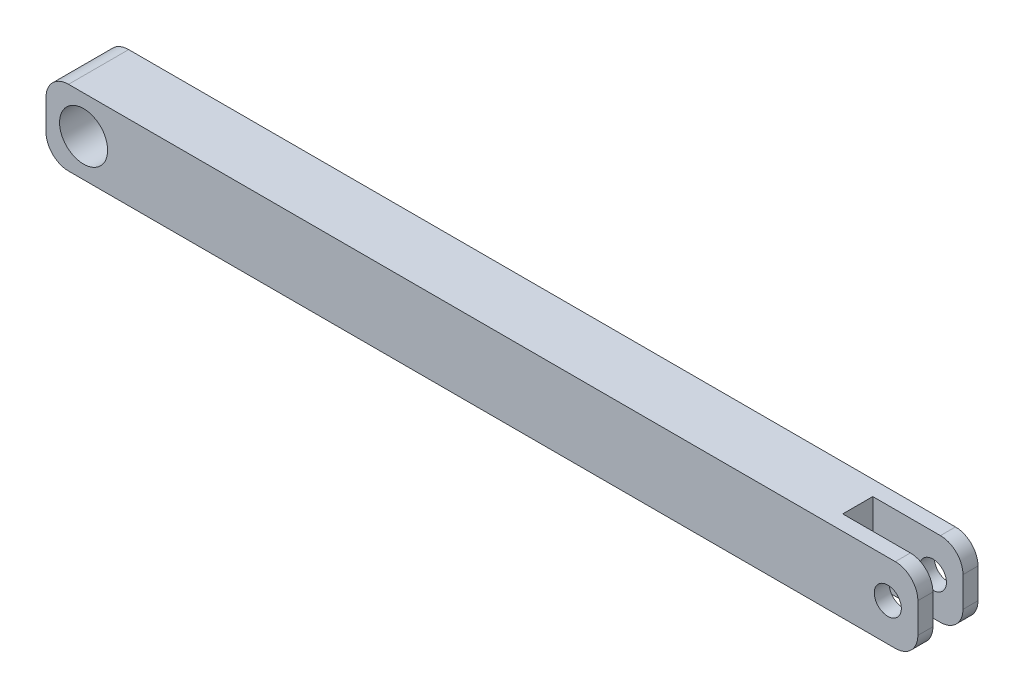
SolidWorks part; units mm, degrees
ref_plane "前视基准面" through (0, 0, 0) normal (0, 0, 1) x (1, 0, 0)
ref_plane "上视基准面" through (0, 0, 0) normal (0, 1, 0) x (1, 0, 0)
ref_plane "右视基准面" through (0, 0, 0) normal (1, 0, 0) x (0, 0, -1)
other "Configuration Table"
sketch "草图5" plane through (0, 0, 0) normal (0, 1, 0) x (1, 0, 0)
  line L0 (0, 0) -> (0, -3)
  line L4 (58, -3) -> (58, 0)
  line L8 (58, 0) -> (0, 0)
  line L9 (0, -3) -> (58, -3)
  dimension "D6" = 3
  dimension "D1" = 58
  dimension "D5" = 3
extrude "凸台-拉伸1" add sketch "草图5" along normal blind 5
sketch "草图6" plane through (0, 0, 3) normal (0, 0, 1) x (1, 0, 0)
  line L2 (0, 5) -> (0, 0) construction
  line L3 (0, 5) -> (58, 5) construction
  circle A0 centre (2.5, 2.5) radius 1.6
  dimension "D1" = 3.2
  dimension "D2" = 2.5
  dimension "D3" = 2.5
extrude "切除-拉伸1" cut sketch "草图6" against normal up to next
sketch "草图7" plane through (0, 0, 0) normal (0, 0, 1) x (1, 0, 0)
  line L0 (58, 5) -> (58, 0) construction
  circle A0 centre (56, 2.5) radius 0.9
  point P6 (58, 2.5)
  dimension "D1" = 1.8
  dimension "D2" = 2
extrude "切除-拉伸2" cut sketch "草图7" along normal up to next
fillet "圆角1" radius 1.5 4 edges at (58, 5, 1.5) (58, 0, 1.5) (0, 0, 1.5) (0, 5, 1.5)
sketch "草图8" plane through (0, 5, 0) normal (0, 1, 0) x (1, 0, 0)
  line L0 (58, 0) -> (58, -3) construction
  line L1 (58, -0.7) -> (52, -0.7)
  line L2 (58, -0.7) -> (58, -2.3)
  line L3 (58, -2.3) -> (52, -2.3)
  line L4 (52, -0.7) -> (52, -2.3)
  point P6 (58, -1.5)
  dimension "D1" = 1.6
  dimension "D2" = 6
extrude "切除-拉伸3" cut sketch "草图8" against normal blind 10
sketch "草图10" plane through (0, 0, 3) normal (0, 0, 1) x (1, 0, 0)
  line L3 (58, 1.5) -> (58, 3.5)
  line L5 (58, 1.5) -> (58, 3.5)
  line L6 (0, 3.5) -> (0, 1.5)
  line L10 (0, 3.5) -> (0, 1.5)
  line L12 (56.5, 5) -> (1.5, 5)
  line L13 (56.5, 5) -> (1.5, 5)
  line L14 (1.5, 0) -> (56.5, 0)
  line L15 (1.5, 0) -> (56.5, 0)
  circle A0 centre (2.5, 2.5) radius 1.6 construction
  circle A1 centre (2.5, 2.5) radius 1.6
  circle A2 centre (56, 2.5) radius 0.9 construction
  circle A3 centre (56, 2.5) radius 0.9
  arc A4 (58, 3.5) -> (56.5, 5) centre (56.5, 3.5) ccw
  arc A5 (1.5, 5) -> (0, 3.5) centre (1.5, 3.5) ccw
  arc A6 (0, 1.5) -> (1.5, 0) centre (1.5, 1.5) ccw
  arc A9 (1.5, 5) -> (0, 3.5) centre (1.5, 3.5) ccw
  arc A10 (0, 1.5) -> (1.5, 0) centre (1.5, 1.5) ccw
  arc A15 (58, 3.5) -> (56.5, 5) centre (56.5, 3.5) ccw
  arc A16 (56.5, 0) -> (58, 1.5) centre (56.5, 1.5) ccw
  arc A17 (56.5, 0) -> (58, 1.5) centre (56.5, 1.5) ccw
  dimension "D1" = 0
extrude "凸台-拉伸2" add sketch "草图10" along normal blind 0.5
sketch "草图11" plane through (0, 0, 0) normal (0, 0, -1) x (-1, 0, 0)
  line L4 (-1.5, 5) -> (-56.5, 5)
  line L5 (-58, 3.5) -> (-58, 1.5)
  line L6 (-56.5, 0) -> (-1.5, 0)
  line L7 (0, 1.5) -> (0, 3.5)
  line L8 (-1.5, 5) -> (-56.5, 5)
  line L9 (-58, 3.5) -> (-58, 1.5)
  line L10 (-56.5, 0) -> (-1.5, 0)
  line L11 (0, 1.5) -> (0, 3.5)
  circle A0 centre (-56, 2.5) radius 0.9 construction
  circle A1 centre (-2.5, 2.5) radius 1.6 construction
  circle A2 centre (-56, 2.5) radius 0.9
  circle A3 centre (-2.5, 2.5) radius 1.6
  arc A4 (-56.5, 5) -> (-58, 3.5) centre (-56.5, 3.5) ccw
  arc A5 (-58, 1.5) -> (-56.5, 0) centre (-56.5, 1.5) ccw
  arc A6 (-1.5, 0) -> (0, 1.5) centre (-1.5, 1.5) ccw
  arc A7 (0, 3.5) -> (-1.5, 5) centre (-1.5, 3.5) ccw
  arc A8 (-56.5, 5) -> (-58, 3.5) centre (-56.5, 3.5) ccw
  arc A9 (-58, 1.5) -> (-56.5, 0) centre (-56.5, 1.5) ccw
  arc A10 (-1.5, 0) -> (0, 1.5) centre (-1.5, 1.5) ccw
  arc A11 (0, 3.5) -> (-1.5, 5) centre (-1.5, 3.5) ccw
  dimension "D1" = 0
extrude "凸台-拉伸3" add sketch "草图11" along normal blind 0.5
sketch "草图12" plane through (0, 0, 0) normal (0, -1, 0) x (1, 0, 0)
  line L0 (52, 2.3) -> (56.5, 2.3) construction
  line L1 (58.4467, 0.5) -> (52, 0.5)
  line L2 (58.4467, 0.5) -> (58.4467, 2.5)
  line L3 (58.4467, 2.5) -> (52, 2.5)
  line L4 (52, 0.5) -> (52, 2.5)
  line L5 (58.4467, 0.5) -> (52, 2.5) construction
  line L6 (58.4467, 2.5) -> (52, 0.5) construction
  line L7 (56.5, 0.7) -> (52, 0.7) construction
  point P0 (55.2233, 1.5)
  dimension "D1" = 0.2
  dimension "D2" = 0.2
extrude "切除-拉伸4" cut sketch "草图12" against normal blind 10
